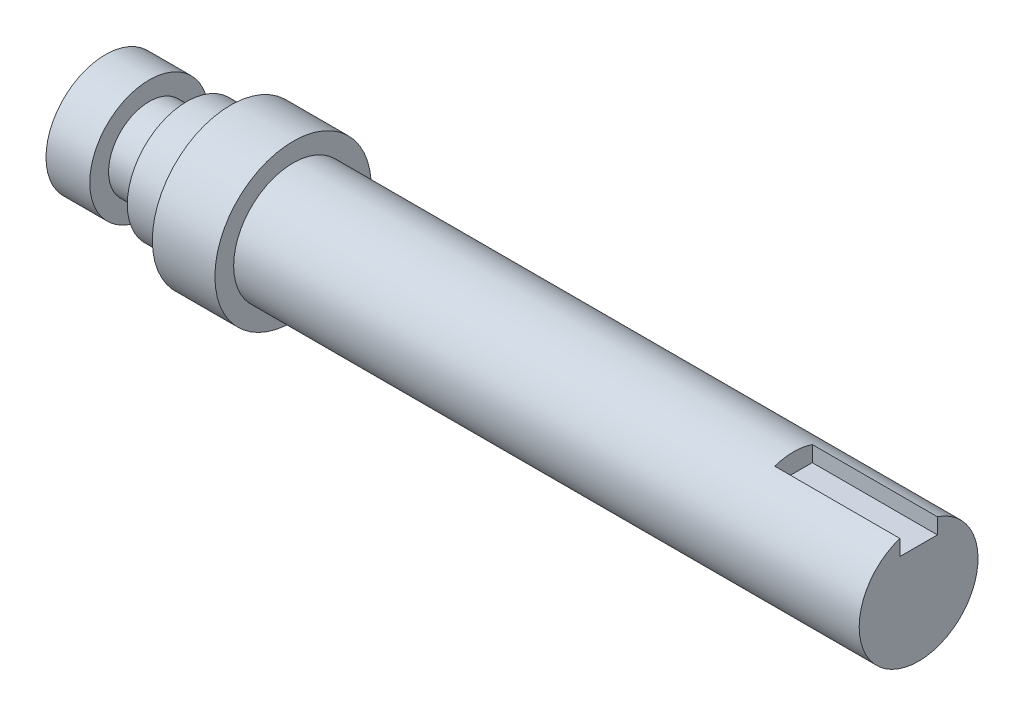
SolidWorks part; units mm, degrees
ref_plane "Front Plane" through (0, 0, 0) normal (0, 0, 1) x (1, 0, 0)
ref_plane "Top Plane" through (0, 0, 0) normal (0, 1, 0) x (1, 0, 0)
ref_plane "Right Plane" through (0, 0, 0) normal (1, 0, 0) x (0, 0, -1)
sketch "Sketch1" plane through (0, 0, 0) normal (0, 0, 1) x (1, 0, 0)
  line L0 (-110, 9.5) -> (-110, 12.5)
  line L1 (0, 0) -> (-130, 0)
  line L2 (0, 0) -> (0, 9.5)
  line L3 (0, 9.5) -> (-100, 9.5)
  line L4 (-130, 0) -> (-130, 9.5)
  line L5 (-110, 12.5) -> (-100, 12.5)
  line L6 (-100, 12.5) -> (-100, 9.5)
  line L7 (-110, 9.5) -> (-130, 9.5)
  line L8 (0.8667, 0) -> (50000.8667, 0) construction
  dimension "D1" = 100
  dimension "D2" = 10
  dimension "D3" = 20
  dimension "D4" = 9.5
  dimension "D5" = 12.5
revolve "Revolve1" add sketch "Sketch1" angle 360 about L8
sketch "Sketch2" plane through (0, 0, 0) normal (0, 0, 1) x (1, 0, 0)
  line L0 (-110, 9.5) -> (-130, 9.5) construction
  line L1 (-123, 9.5) -> (-117, 9.5)
  line L2 (-123, 9.5) -> (-123, 6.5)
  line L3 (-123, 6.5) -> (-117, 6.5)
  line L4 (-117, 9.5) -> (-117, 6.5)
  line L5 (-130, 9.5) -> (-130, -9.5) construction
  line L6 (-130, 0) -> (-110, 0) construction
  line L7 (-110, 12.5) -> (-110, -12.5) construction
  dimension "D1" = 6
  dimension "D2" = 3
  dimension "D3" = 7
revolve "Cut-Revolve1" cut sketch "Sketch2" angle 360 about L6
sketch "Sketch3" plane through (0, 0, 0) normal (0, 0, 1) x (1, 0, 0)
  line L0 (0, -9.5) -> (0, 9.5) construction
  line L1 (0, 6.5) -> (-20, 6.5)
  line L2 (0, 6.5) -> (0, 9.5)
  line L3 (0, 9.5) -> (-20, 9.5)
  line L4 (-20, 6.5) -> (-20, 9.5)
  line L5 (0, 9.5) -> (-100, 9.5) construction
  dimension "D1" = 20
  dimension "D2" = 3
extrude "Cut-Extrude1" cut sketch "Sketch3" against normal mid plane 6
